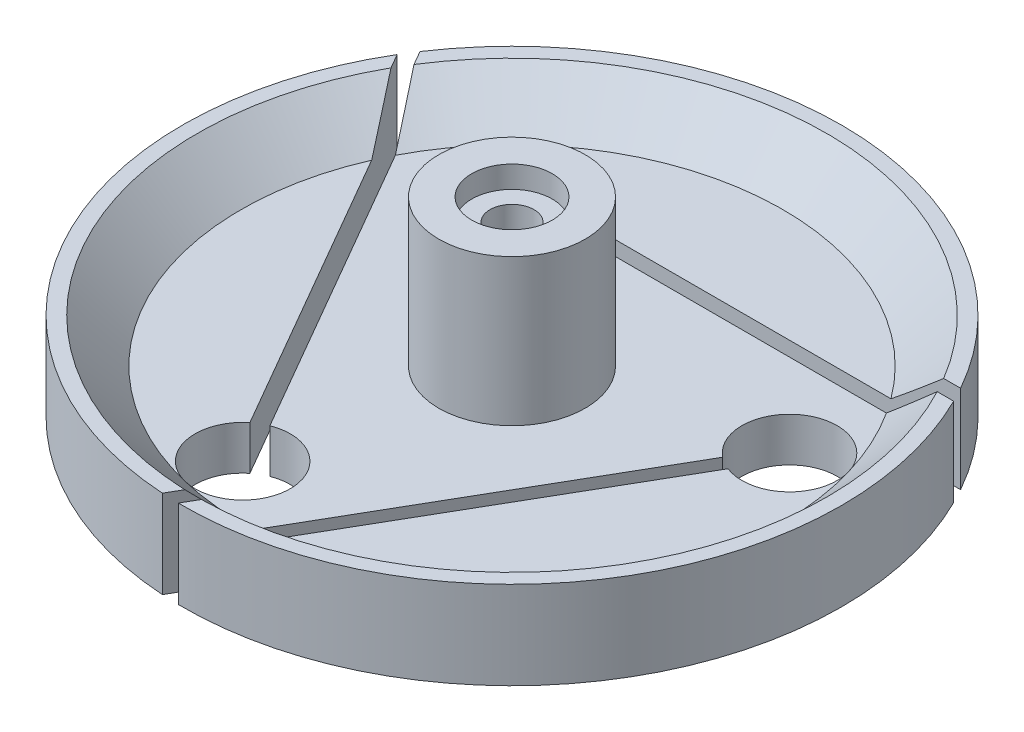
SolidWorks part; units mm, degrees
ref_plane "前视基准面" through (0, 0, 0) normal (0, 0, 1) x (1, 0, 0)
ref_plane "上视基准面" through (0, 0, 0) normal (0, 1, 0) x (1, 0, 0)
ref_plane "右视基准面" through (0, 0, 0) normal (1, 0, 0) x (0, 0, -1)
other "Configuration Table"
sketch "草图1" plane through (0, 0, 0) normal (0, 0, 1) x (1, 0, 0)
  line L0 (0, 83.7288) -> (0, -65.0712) construction
  line L1 (10, 26) -> (10, 6)
  line L2 (10, 6) -> (37, 6)
  line L3 (37, 6) -> (43, 12)
  line L4 (43, 12) -> (45, 12)
  line L5 (45, 12) -> (45, 0)
  line L6 (45, 0) -> (3, 0)
  line L7 (3, 0) -> (3, 23)
  line L8 (3, 23) -> (5.5, 23)
  line L9 (5.5, 23) -> (5.5, 26)
  line L10 (5.5, 26) -> (10, 26)
  point P11 (4.25, 23)
  dimension "D1" = 3
  dimension "D2" = 3
  dimension "D3" = 20
  dimension "D4" = 2
  dimension "D5" = 135
  dimension "D6" = 11
  dimension "D7" = 26
  dimension "D8" = 90
  dimension "D9" = 12
  dimension "D10" = 6
revolve "旋转1" add sketch "草图1" angle 360 about L0
sketch "草图2" plane through (0, 6, 0) normal (0, 1, 0) x (1, 0, 0)
  line L0 (-22.119, 21) -> (54.5409, 21) construction
  line L1 (-15.6964, 22) -> (39.2556, 22)
  line L2 (-15.6964, 20) -> (40.3113, 20)
  arc A0 (-15.6964, 22) -> (-15.6964, 20) centre (-22.119, 21) ccw
  circle A1 centre (0, 0) radius 37 construction
  arc A2 (40.3113, 20) -> (39.2556, 22) centre (0, 0) ccw
  circle A3 centre (0, 0) radius 45 construction
  point P1 (0, 0)
  dimension "D3" = 6.5
  dimension "D1" = 21
  dimension "D2" = 2
extrude "切除-拉伸1" cut sketch "草图2" against normal through all both and the other way through all
pattern_circular "阵列(圆周)1" count 3 over 360 about axis through (0, 0, 0) along (0, 1, 0) of "切除-拉伸1"
